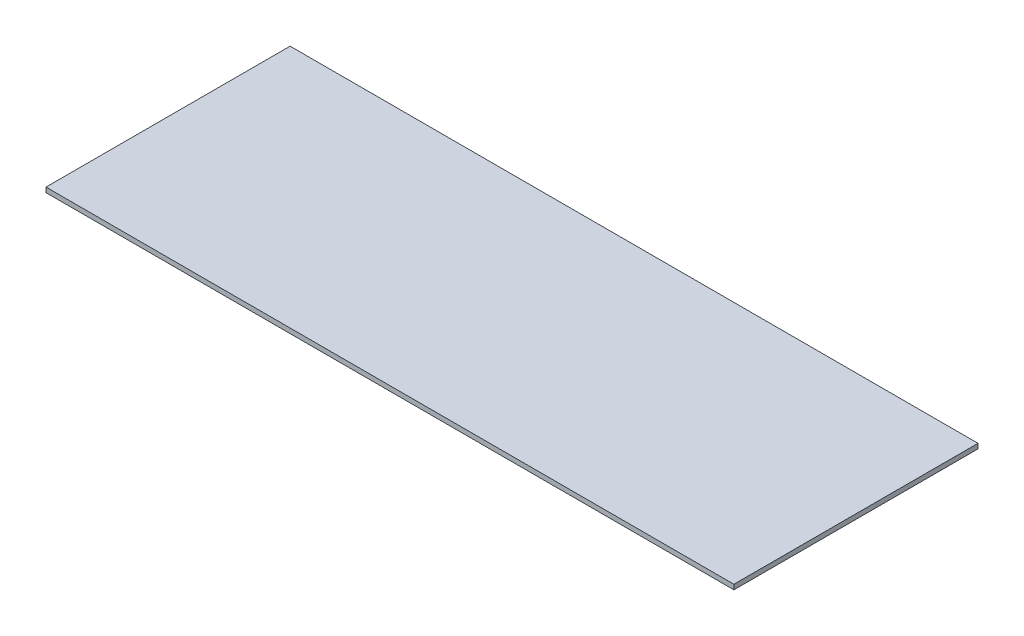
SolidWorks part; units mm, degrees
material "Pine"
ref_plane "Front Plane" through (0, 0, 0) normal (0, 0, 1) x (1, 0, 0)
ref_plane "Top Plane" through (0, 0, 0) normal (0, 1, 0) x (1, 0, 0)
ref_plane "Right Plane" through (0, 0, 0) normal (1, 0, 0) x (0, 0, -1)
sketch "Sketch1" plane through (0, 0, 0) normal (0, 1, 0) x (1, 0, 0)
  line L1 (-393.7, -139.7) -> (393.7, -139.7)
  line L2 (-393.7, -139.7) -> (-393.7, 139.7)
  line L3 (-393.7, 139.7) -> (393.7, 139.7)
  line L4 (393.7, -139.7) -> (393.7, 139.7)
  line L5 (-393.7, -139.7) -> (393.7, 139.7) construction
  line L6 (-393.7, 139.7) -> (393.7, -139.7) construction
  point P0 (0, 0)
  dimension "D1" = 787.4
  dimension "D2" = 279.4
extrude "Boss-Extrude1" add sketch "Sketch1" along normal blind 5.5562
